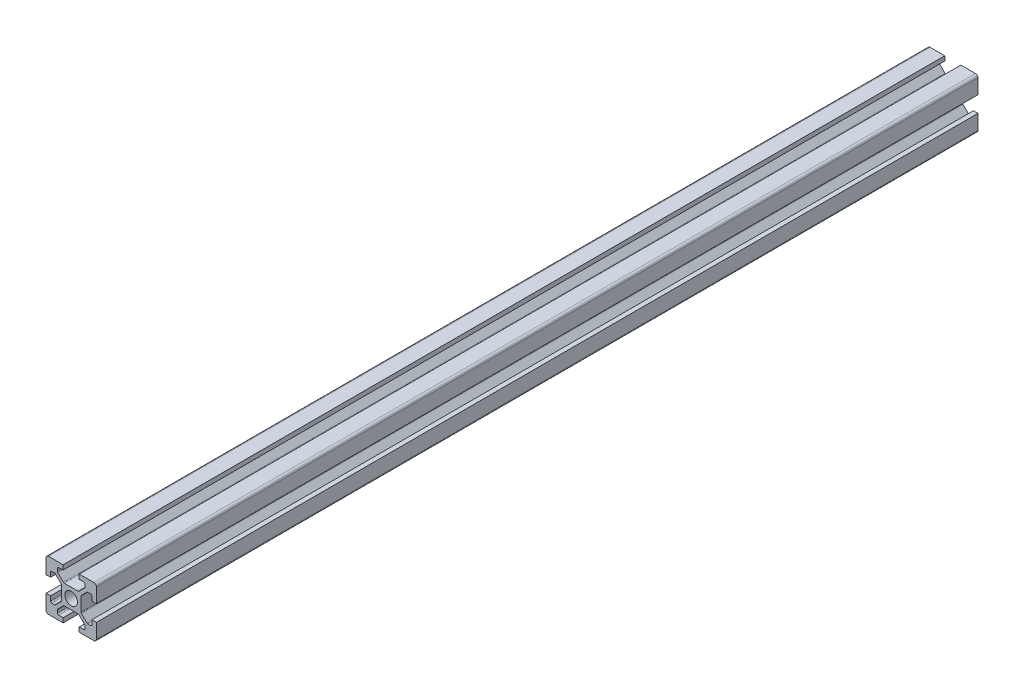
SolidWorks part; units mm, degrees
material "1060 Alloy"
ref_plane "Front Plane" through (0, 0, 0) normal (0, 0, 1) x (1, 0, 0)
ref_plane "Top Plane" through (0, 0, 0) normal (0, 1, 0) x (1, 0, 0)
ref_plane "Right Plane" through (0, 0, 0) normal (1, 0, 0) x (0, 0, -1)
sketch "Sketch1" plane through (0, 0, 0) normal (0, 0, 1) x (1, 0, 0)
  line L0 (20, 0) -> (-8.059, 28.059) construction
  line L1 (0, 0) -> (6.8, 0)
  line L2 (0, 0) -> (0, 6.8)
  line L3 (0, 20) -> (6.8, 20)
  line L4 (20, 0) -> (20, 6.8)
  line L5 (6.8, 20) -> (6.8, 18.2)
  line L6 (20, 20) -> (8.2322, 8.2322) construction
  line L7 (12.95, 6.1) -> (7.05, 6.1)
  line L8 (13.9, 7.05) -> (13.9, 12.95)
  line L9 (12.95, 13.9) -> (7.05, 13.9)
  line L10 (6.1, 7.05) -> (6.1, 12.95)
  line L11 (13.9, 6.1) -> (6.1, 13.9) construction
  line L12 (13.9, 13.9) -> (6.1, 6.1) construction
  line L13 (4.55, 16.4) -> (7.05, 13.9)
  line L14 (13.2, 18.2) -> (13.2, 20)
  line L15 (1.8, 6.8) -> (0, 6.8)
  line L16 (0, 13.2) -> (0, 20)
  line L17 (0, 13.2) -> (1.8, 13.2)
  line L18 (10, 10) -> (10, 13.9) construction
  line L19 (16.4, 4.55) -> (13.9, 7.05)
  line L20 (4.55, 16.4) -> (4.55, 18.2)
  line L21 (4.55, 18.2) -> (6.8, 18.2)
  line L22 (13.2, 18.2) -> (15.45, 18.2)
  line L23 (15.45, 18.2) -> (15.45, 16.4)
  line L24 (15.45, 16.4) -> (12.95, 13.9)
  line L25 (16.4, 4.55) -> (18.2, 4.55)
  line L26 (18.2, 4.55) -> (18.2, 6.8)
  line L27 (20, 6.8) -> (18.2, 6.8)
  line L28 (18.2, 13.2) -> (20, 13.2)
  line L29 (18.2, 13.2) -> (18.2, 15.45)
  line L30 (18.2, 15.45) -> (16.4, 15.45)
  line L31 (16.4, 15.45) -> (13.9, 12.95)
  line L32 (1.8, 4.55) -> (3.6, 4.55)
  line L33 (3.6, 15.45) -> (6.1, 12.95)
  line L34 (3.6, 15.45) -> (1.8, 15.45)
  line L35 (1.8, 15.45) -> (1.8, 13.2)
  line L36 (0, 13.2) -> (1.8, 13.2)
  line L37 (1.8, 6.8) -> (0, 6.8)
  line L38 (3.6, 4.55) -> (6.1, 7.05)
  line L39 (1.8, 6.8) -> (1.8, 4.55)
  line L40 (15.45, 3.6) -> (12.95, 6.1)
  line L41 (4.55, 3.6) -> (7.05, 6.1)
  line L42 (4.55, 1.8) -> (4.55, 3.6)
  line L43 (6.8, 1.8) -> (4.55, 1.8)
  line L44 (6.8, 1.8) -> (6.8, 0)
  line L45 (15.45, 3.6) -> (15.45, 1.8)
  line L46 (15.45, 1.8) -> (13.2, 1.8)
  line L47 (13.2, 0) -> (13.2, 1.8)
  line L48 (13.2, 20) -> (20, 20)
  line L49 (20, 13.2) -> (20, 20)
  line L50 (13.2, 0) -> (20, 0)
  line L51 (6.1, 6.1) -> (-5.5045, -5.5045) construction
  circle A0 centre (10, 10) radius 2.5
  point P25 (10, 16.4)
  point P39 (13.2, 19.1)
  point P46 (0.9, 6.8)
  dimension "D3" = 5
  dimension "D2" = 20
  dimension "D4" = 7.8
  dimension "D5" = 7.8
  dimension "D6" = 6.8
  dimension "D7" = 6.8
  dimension "D8" = 1.8
  dimension "D9" = 10.9
  dimension "D10" = 1.8
  dimension "D11" = 10.9
  dimension "D12" = 20
extrude "Boss-Extrude1" add sketch "Sketch1" along normal blind 350 contours L47 L50 L4 L27 L26 L25 L19 L8 L31 L30 L29 L28 L49 L48 L14 L22 L23 L24 L9 L13 L20 L21 L5 L3 L16 L17 L35 L34 L33 L10 L38 L32 L39 L15 L2 L1 L44 L43 L42 L41 L7 L40 L45 L46 A0
fillet "Fillet1" radius 1 4 edges at (20, 20, 175) (20, 0, 175) (0, 0, 175) (0, 20, 175)
fillet "Fillet2" radius 0.5 6 edges at (4.55, 18.2, 175) (4.55, 16.4, 175) (7.05, 13.9, 175) (15.45, 18.2, 175) (15.45, 16.4, 175) (12.95, 13.9, 175)
fillet "Fillet3" radius 0.5 6 edges at (18.2, 15.45, 175) (16.4, 15.45, 175) (13.9, 12.95, 175) (18.2, 4.55, 175) (13.9, 7.05, 175) (16.4, 4.55, 175)
fillet "Fillet4" radius 0.5 6 edges at (1.8, 15.45, 175) (3.6, 15.45, 175) (6.1, 12.95, 175) (3.6, 4.55, 175) (1.8, 4.55, 175) (6.1, 7.05, 175)
fillet "Fillet5" radius 0.5 6 edges at (7.05, 6.1, 175) (4.55, 3.6, 175) (4.55, 1.8, 175) (15.45, 1.8, 175) (15.45, 3.6, 175) (12.95, 6.1, 175)
